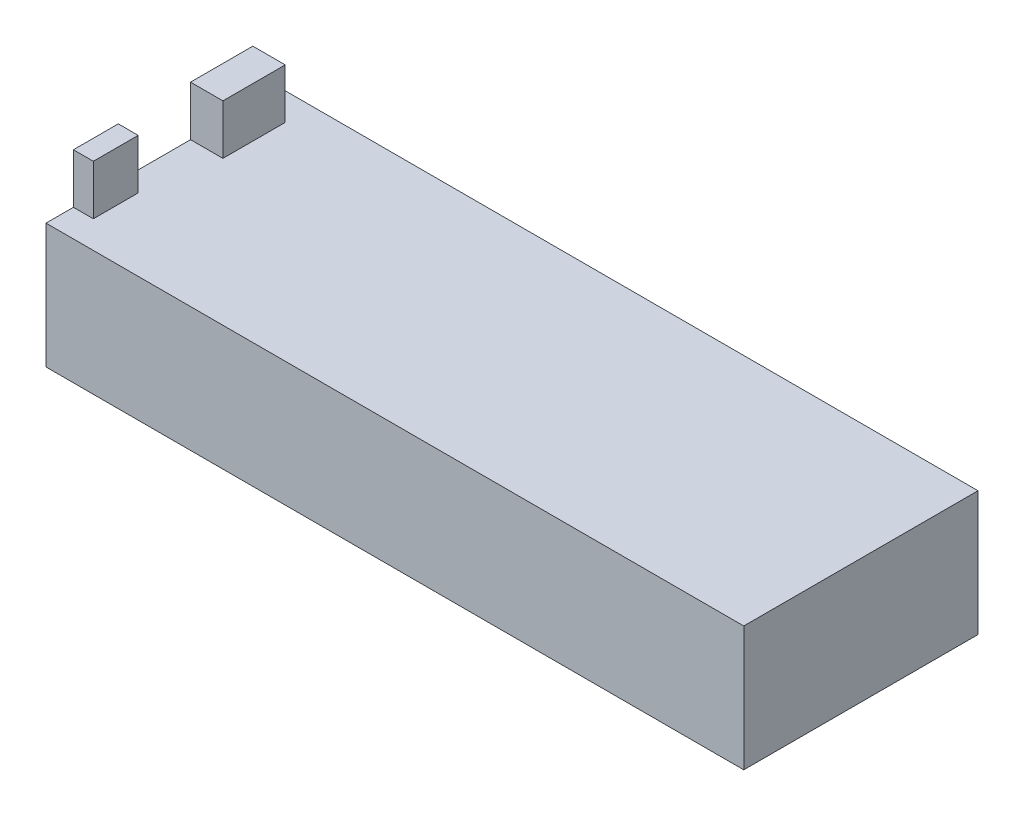
SolidWorks part; units mm, degrees
ref_plane "Front Plane" through (0, 0, 0) normal (0, 0, 1) x (1, 0, 0)
ref_plane "Top Plane" through (0, 0, 0) normal (0, 1, 0) x (1, 0, 0)
ref_plane "Right Plane" through (0, 0, 0) normal (1, 0, 0) x (0, 0, -1)
sketch "Sketch1" plane through (0, 0, 0) normal (0, 1, 0) x (1, 0, 0)
  line L1 (-70, -23.5) -> (70, -23.5)
  line L2 (-70, -23.5) -> (-70, 23.5)
  line L3 (-70, 23.5) -> (70, 23.5)
  line L4 (70, -23.5) -> (70, 23.5)
  line L5 (-70, -23.5) -> (70, 23.5) construction
  line L6 (-70, 23.5) -> (70, -23.5) construction
  point P0 (0, 0)
  dimension "D1" = 140
  dimension "D2" = 47
extrude "Boss-Extrude1" add sketch "Sketch1" along normal blind 25
sketch "Sketch2" plane through (0, 25, 0) normal (0, 1, 0) x (1, 0, 0)
  line L0 (-70, 23.5) -> (-70, -23.5) construction
  line L1 (-70, 18) -> (-63.5, 18)
  line L2 (-70, 18) -> (-70, 5.5)
  line L3 (-70, 5.5) -> (-63.5, 5.5)
  line L4 (-63.5, 18) -> (-63.5, 5.5)
  line L5 (70, 23.5) -> (-70, 23.5) construction
  line L6 (-70, -9) -> (-66, -9)
  line L7 (-70, -9) -> (-70, -18)
  line L8 (-70, -18) -> (-66, -18)
  line L9 (-66, -9) -> (-66, -18)
  line L10 (-70, -23.5) -> (70, -23.5) construction
  dimension "D1" = 6.5
  dimension "D2" = 12.5
  dimension "D3" = 5.5
  dimension "D4" = 4
  dimension "D5" = 9
  dimension "D6" = 5.5
extrude "Boss-Extrude2" add sketch "Sketch2" along normal blind 10
